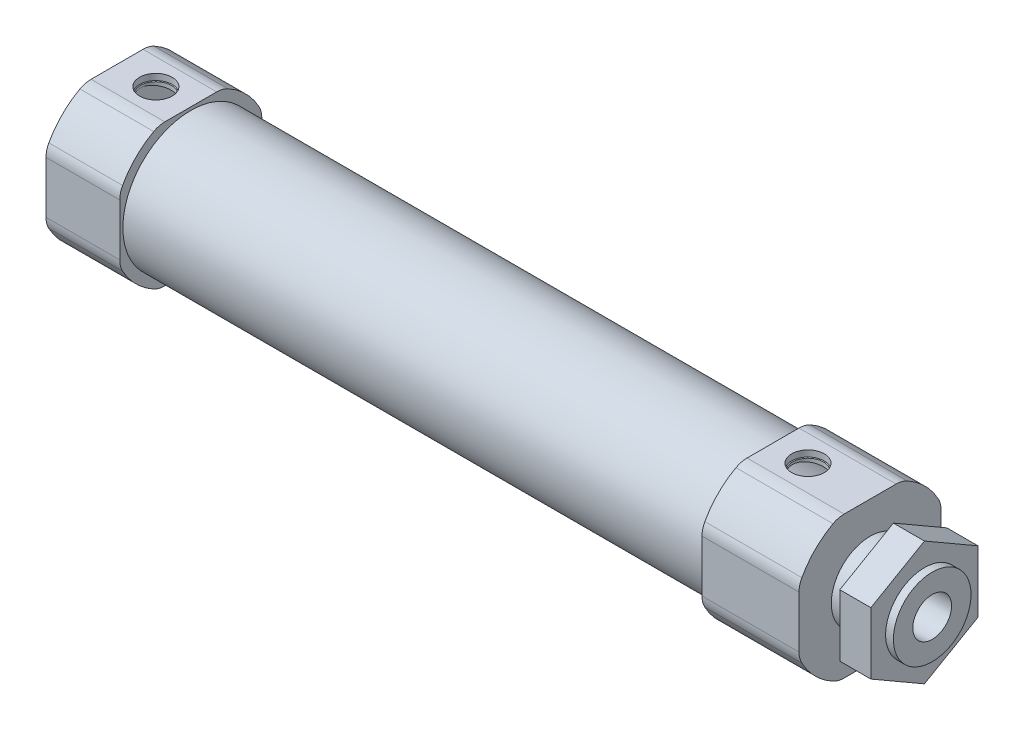
SolidWorks part; units mm, degrees
material "6061-T6 (SS)"
ref_plane "前视基准面" through (0, 0, 0) normal (0, 0, 1) x (1, 0, 0)
ref_plane "上视基准面" through (0, 0, 0) normal (0, 1, 0) x (1, 0, 0)
ref_plane "右视基准面" through (0, 0, 0) normal (1, 0, 0) x (0, 0, -1)
sketch "主筒" plane through (0, 0, 0) normal (1, 0, 0) x (0, 0, -1)
  circle A0 centre (0, 0) radius 8.75
  dimension "D1" = 17.5
extrude "主缸筒" add sketch "主筒" along normal blind 97
sketch "前头1" plane through (97, 0, 0) normal (1, 0, 0) x (0, 0, -1)
  line L1 (-9.15, 9.15) -> (9.15, 9.15)
  line L2 (-9.15, 9.15) -> (-9.15, -9.15)
  line L3 (-9.15, -9.15) -> (9.15, -9.15)
  line L4 (9.15, 9.15) -> (9.15, -9.15)
  line L5 (-9.15, 9.15) -> (9.15, -9.15) construction
  line L6 (-9.15, -9.15) -> (9.15, 9.15) construction
  circle A0 centre (0, 0) radius 10
  point P0 (0, 0)
  circle M3 centre (0, 0) radius 8.75
  dimension "D2" = 20
  dimension "D1" = 18.3
extrude "前头" add sketch "前头1" against normal blind 12.5 contours L2 A0 L3 M3
sketch "后头1" plane through (0, 0, 0) normal (-1, 0, 0) x (0, 0, 1)
  line L1 (-9.15, 9.15) -> (9.15, 9.15)
  line L2 (-9.15, 9.15) -> (-9.15, -9.15)
  line L3 (-9.15, -9.15) -> (9.15, -9.15)
  line L4 (9.15, 9.15) -> (9.15, -9.15)
  line L5 (-9.15, 9.15) -> (9.15, -9.15) construction
  line L6 (-9.15, -9.15) -> (9.15, 9.15) construction
  circle A0 centre (0, 0) radius 10
  point P0 (0, 0)
  circle M9 centre (0, 0) radius 8.75
  dimension "D2" = 20
  dimension "D1" = 18.3
extrude "后头" add sketch "后头1" against normal blind 9.5 contours L4 A0 L1 L2 L3 M9
sketch "气管接头1" plane through (0, 9.15, 0) normal (0, 1, 0) x (1, 0, 0)
  line L0 (0, 0) -> (97, 0) construction
  line L1 (97, -4.0345) -> (97, 4.0345) construction
  line L2 (0, 4.0345) -> (0, -4.0345) construction
  circle A0 centre (5, 0) radius 2
  circle A1 centre (89, 0) radius 2
  dimension "D1" = 5
  dimension "D3" = 4
  dimension "D2" = 8
extrude "气管接头" cut sketch "气管接头1" against normal blind 10
hole_wizard "外孔" positions "3D草图1" profile "草图5" tap size "M5" standard "GB"
sketch3d "3D草图1"
  point P0 (5, 9.15, 0)
  point P3 (89, 9.15, 0)
sketch "草图5" plane through (5, 9.15, 0) normal (1, 0, 0) x (0, 0, 1)
  line L0 (0, 0) -> (0, 2.0618)
  line L1 (0, 2.0618) -> (2.1, 0.8)
  line L2 (2.1, 0.8) -> (2.1, 0)
  line L5 (2.1, 0) -> (0, 0)
  line L10 (0, 2.0618) -> (-2.1, 0.8) construction
  line L11 (0, -6.35) -> (0, 107.95) construction
  dimension "螺纹孔钻头直径" = 4.2
  dimension "螺纹孔钻头深度" = 0.8
  dimension "导头角度" = 118
cosmetic thread "孔螺蚊线1" parameters "D1"=0.8, "D2"=5
cosmetic thread "孔螺蚊线3" parameters "D1"=0.8, "D2"=5
sketch "内腔1" plane through (97, 0, 0) normal (1, 0, 0) x (0, 0, -1)
  circle A0 centre (0, 0) radius 8
  dimension "D1" = 16
extrude "切除-拉伸3" cut sketch "内腔1" against normal offset from surface (91 mm away) 3 from offset 3 up to face at (0, 0, 0) offset against normal yes
sketch "气缸头1" plane through (97, 0, 0) normal (1, 0, 0) x (0, 0, -1)
  circle A0 centre (0, 0) radius 5
  dimension "D1" = 10
extrude "气缸头" add sketch "气缸头1" along normal blind 8
cosmetic thread "装饰螺纹线1" parameters "D1"=5, "D2"=6.647
sketch "内芯1" plane through (105, 0, 0) normal (1, 0, 0) x (0, 0, -1)
  circle A0 centre (0, 0) radius 2.5
  dimension "D1" = 5
extrude "内芯" cut sketch "内芯1" against normal up to next
fillet "圆角2" radius 3 8 edges at (4.75, -4.0345, 9.15) (4.75, 4.0345, 9.15) (4.75, 4.0345, -9.15) (4.75, -4.0345, -9.15) (4.75, -9.15, -4.0345) (4.75, -9.15, 4.0345) (4.75, 9.15, 4.0345) (4.75, 9.15, -4.0345)
fillet "圆角3" radius 3 8 edges at (90.75, -4.0345, -9.15) (90.75, 4.0345, -9.15) (90.75, 9.15, -4.0345) (90.75, 9.15, 4.0345) (90.75, 4.0345, 9.15) (90.75, -4.0345, 9.15) (90.75, -9.15, 4.0345) (90.75, -9.15, -4.0345)
sketch "草图6" plane through (97, 0, 0) normal (1, 0, 0) x (0, 0, -1)
  line L1 (0, -7.9674) -> (6.9, -3.9837)
  line L2 (6.9, -3.9837) -> (6.9, 3.9837)
  line L3 (6.9, 3.9837) -> (0, 7.9674)
  line L4 (0, 7.9674) -> (-6.9, 3.9837)
  line L5 (-6.9, 3.9837) -> (-6.9, -3.9837)
  line L6 (-6.9, -3.9837) -> (0, -7.9674)
  circle A0 centre (0, 0) radius 6.9 construction
  circle A1 centre (0, 0) radius 5 construction
  circle A2 centre (0, 0) radius 5
  point P1 (6.7552, 0)
  point P10 (0, -7.1194)
  point P11 (0, 0)
  dimension "D1" = 13.8
extrude "凸台-拉伸1" add sketch "草图6" along normal blind 4 from offset 3 separate body
equation "\"行程l\"= 50"
equation "\"D1@主缸筒\"=\"行程l\"+47"
equation "\"行程2\"= 200"
